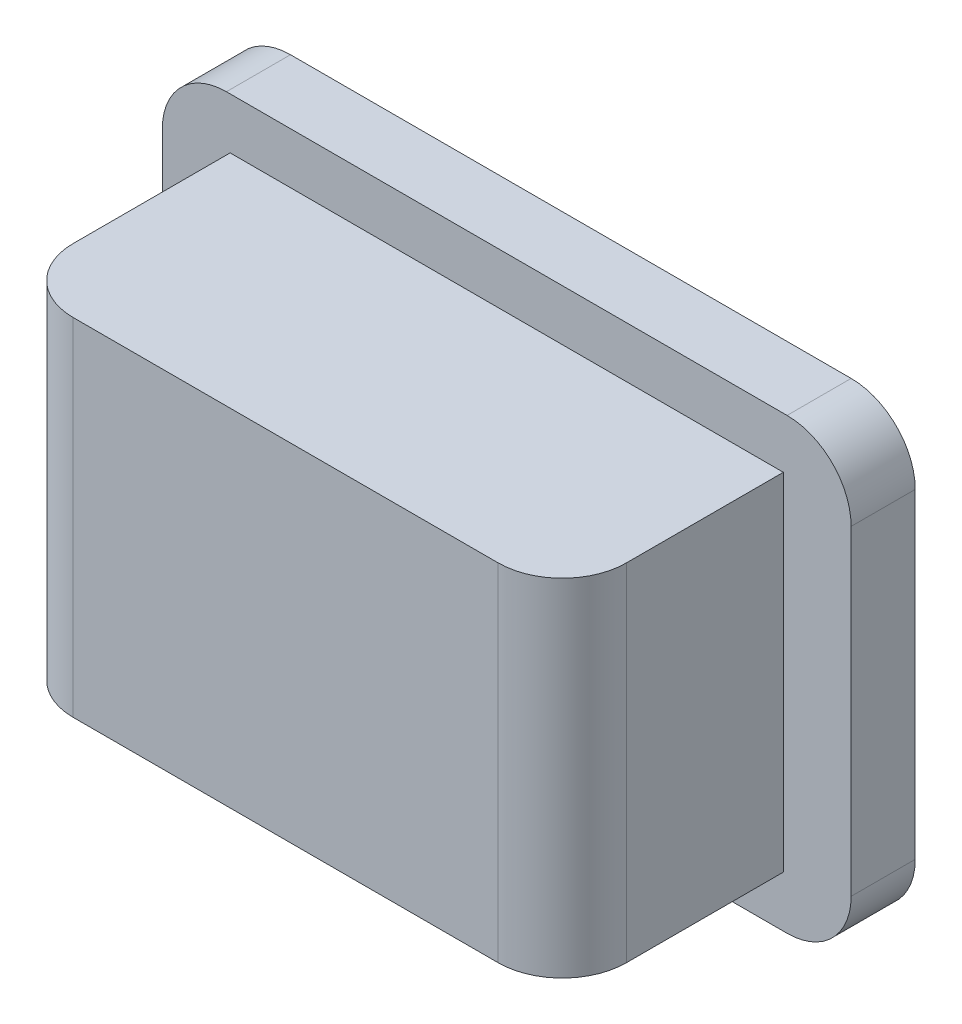
SolidWorks part; units mm, degrees
ref_plane "Front Plane" through (0, 0, 0) normal (0, 0, 1) x (1, 0, 0)
ref_plane "Top Plane" through (0, 0, 0) normal (0, 1, 0) x (1, 0, 0)
ref_plane "Right Plane" through (0, 0, 0) normal (1, 0, 0) x (0, 0, -1)
sketch "Sketch1" plane through (0, 0, 0) normal (0, 0, 1) x (1, 0, 0)
  line L1 (-8.75, -7) -> (8.75, -7)
  line L2 (-10.75, -5) -> (-10.75, 5)
  line L3 (-8.75, 7) -> (8.75, 7)
  line L4 (10.75, -5) -> (10.75, 5)
  line L5 (-10.75, -7) -> (10.75, 7) construction
  line L6 (-10.75, 7) -> (10.75, -7) construction
  arc A0 (10.75, -5) -> (8.75, -7) centre (8.75, -5) cw
  arc A1 (8.75, 7) -> (10.75, 5) centre (8.75, 5) cw
  arc A2 (-10.75, -5) -> (-8.75, -7) centre (-8.75, -5) ccw
  arc A3 (-8.75, 7) -> (-10.75, 5) centre (-8.75, 5) ccw
  point P0 (0, 0)
  dimension "D3" = 2
  dimension "D1" = 14
  dimension "D2" = 21.5
extrude "Boss-Extrude1" add sketch "Sketch1" along normal blind 2
sketch "Sketch2" plane through (0, 0, 2) normal (0, 0, 1) x (1, 0, 0)
  line L1 (-8.6337, -5.4044) -> (8.6337, -5.4044)
  line L2 (-8.6337, -5.4044) -> (-8.6337, 5.4044)
  line L3 (-8.6337, 5.4044) -> (8.6337, 5.4044)
  line L4 (8.6337, -5.4044) -> (8.6337, 5.4044)
  line L5 (-8.6337, -5.4044) -> (8.6337, 5.4044) construction
  line L6 (-8.6337, 5.4044) -> (8.6337, -5.4044) construction
  point P0 (0, 0)
extrude "Boss-Extrude2" add sketch "Sketch2" along normal blind 6.9
fillet "Fillet3" radius 2 2 edges at (8.6337, 0, 8.9) (-8.6337, 0, 8.9)
